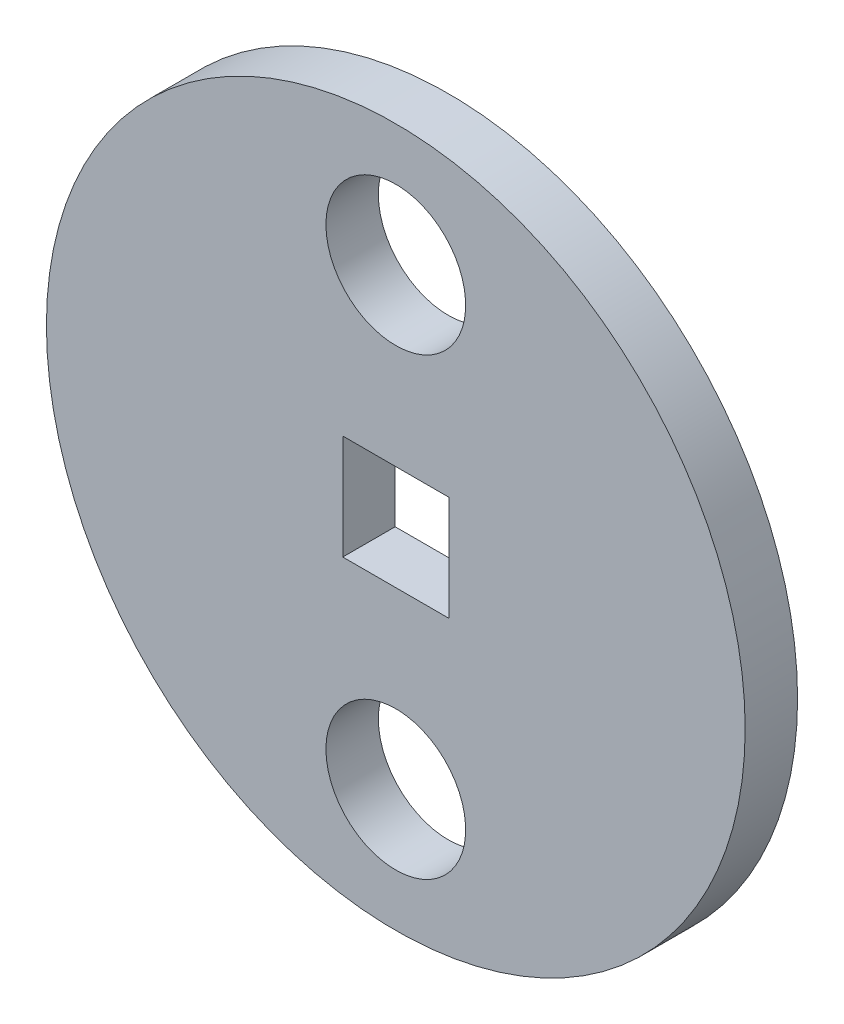
SolidWorks part; units mm, degrees
ref_plane "Front Plane" through (0, 0, 0) normal (0, 0, 1) x (1, 0, 0)
ref_plane "Top Plane" through (0, 0, 0) normal (0, 1, 0) x (1, 0, 0)
ref_plane "Right Plane" through (0, 0, 0) normal (1, 0, 0) x (0, 0, -1)
sketch "Sketch1" plane through (0, 0, 0) normal (0, 0, 1) x (1, 0, 0)
  line L0 (0, 25.4) -> (0, 7.62) construction
  line L2 (-3.8553, 3.81) -> (3.8553, 3.81)
  line L3 (-3.8553, 3.81) -> (-3.8553, -3.81)
  line L4 (-3.8553, -3.81) -> (3.8553, -3.81)
  line L5 (3.8553, 3.81) -> (3.8553, -3.81)
  line L6 (-3.8553, 3.81) -> (3.8553, -3.81) construction
  line L7 (-3.8553, -3.81) -> (3.8553, 3.81) construction
  circle A0 centre (0, 0) radius 25.4
  circle A1 centre (0, 0) radius 7.62 construction
  circle A2 centre (0, 16.51) radius 5.08
  circle A3 centre (0, -16.51) radius 5.08
  point P11 (0, 0)
  point P18 (0, 0)
  point P19 (0, 0)
  dimension "D1" = 15.24
  dimension "D2" = 10.16
  dimension "D4" = 50.8
  dimension "D3" = 7.62
  dimension "D5" = 2
extrude "Boss-Extrude1" add sketch "Sketch1" along normal blind 3.81
